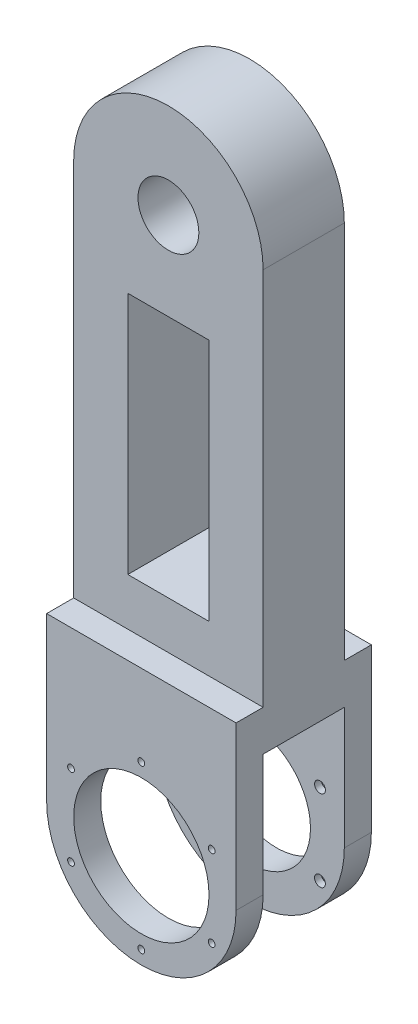
SolidWorks part; units mm, degrees
ref_plane "前视基准面" through (0, 0, 0) normal (0, 0, 1) x (1, 0, 0)
ref_plane "上视基准面" through (0, 0, 0) normal (0, 1, 0) x (1, 0, 0)
ref_plane "右视基准面" through (0, 0, 0) normal (1, 0, 0) x (0, 0, -1)
other "Configuration Table"
sketch "草图1" plane through (0, 0, 0) normal (0, 0, 1) x (1, 0, 0)
  line L1 (-70, -175) -> (70, -175)
  line L2 (-70, -175) -> (-70, 175)
  line L3 (-70, 175) -> (70, 175)
  line L4 (70, -175) -> (70, 175)
  line L5 (-70, -175) -> (70, 175) construction
  line L6 (-70, 175) -> (70, -175) construction
  point P0 (0, 0)
  dimension "D1" = 350
  dimension "D2" = 140
extrude "凸台-拉伸1" add sketch "草图1" along normal blind 60
sketch "草图2" plane through (0, 0, 60) normal (0, 0, 1) x (1, 0, 0)
  line L0 (70, -175) -> (70, 175) construction
  line L1 (-70, 175) -> (70, 175)
  line L2 (-70, 175) -> (-70, 35)
  line L3 (-70, 35) -> (70, 35)
  line L4 (70, 175) -> (70, 35)
  circle A0 centre (0, 105) radius 70
  line M7 (70, 175) -> (-70, 175)
  line M8 (-70, 175) -> (-70, -175)
  dimension "D2" = 140
  dimension "D1" = 140
extrude "切除-拉伸1" cut sketch "草图2" against normal up to next contours A0 L1 M8 | A0 L4 M7
sketch "草图3" plane through (0, 0, 60) normal (0, 0, 1) x (1, 0, 0)
  arc A0 (70, 105) -> (-70, 105) centre (0, 105) ccw construction
  arc A1 (70, 105) -> (-70, 105) centre (0, 105) ccw
  circle A2 centre (0, 105) radius 25
  dimension "D1" = 50
sketch "草图4" plane through (0, -175, 0) normal (0, -1, 0) x (1, 0, 0)
  line L0 (-70, 60) -> (70, 0) construction
  line L1 (-70, 0) -> (70, 60) construction
  line L3 (-70, -20) -> (70, -20)
  line L4 (-70, 0) -> (70, 0)
  line L5 (70, 0) -> (70, 60)
  line L6 (70, 60) -> (-70, 60)
  line L7 (-70, 60) -> (-70, 0)
  line L8 (-70, 0) -> (70, 0)
  line L9 (70, 0) -> (70, 60)
  line L10 (70, 60) -> (-70, 60)
  line L11 (-70, 60) -> (-70, 0)
  line L12 (-70, -20) -> (-70, 80)
  line L13 (-70, 80) -> (70, 80)
  line L14 (70, -20) -> (70, 80)
  line L15 (-70, -20) -> (70, 80) construction
  line L16 (-70, 80) -> (70, -20) construction
  point P2 (0, 30)
  dimension "D2" = 140
  dimension "D3" = 100
  dimension "D1" = 0
extrude "凸台-拉伸3" add sketch "草图4" along normal blind 30 contours L3 L14 L13 L12
sketch "草图5" plane through (0, -205, 0) normal (0, -1, 0) x (1, 0, 0)
  line L0 (70, 60) -> (-70, 60) construction
  line L1 (-70, 60) -> (-70, 80) construction
  line L2 (-70, 80) -> (70, 80) construction
  line L3 (70, 80) -> (70, 60) construction
  line L4 (-70, 80) -> (-70, -20)
  line L5 (-70, -20) -> (70, -20)
  line L6 (70, -20) -> (70, 80)
  line L7 (70, 80) -> (-70, 80)
  line L8 (-70, 80) -> (-70, -20)
  line L9 (-70, -20) -> (70, -20)
  line L10 (70, -20) -> (70, 80)
  line L11 (70, 80) -> (-70, 80)
  line L12 (-70, -20) -> (-70, 0) construction
  line L13 (-70, 0) -> (70, 0) construction
  line L14 (70, 0) -> (70, -20) construction
  line L15 (70, -20) -> (-70, -20) construction
  line L16 (70, 60) -> (-70, 60)
  line L17 (-70, 60) -> (-70, 80)
  line L18 (-70, 80) -> (70, 80)
  line L19 (70, 80) -> (70, 60)
  line L20 (-70, -20) -> (-70, 0)
  line L21 (-70, 0) -> (70, 0)
  line L22 (70, 0) -> (70, -20)
  line L23 (70, -20) -> (-70, -20)
  line M5 (-70, 80) -> (-70, -20)
  line M6 (-70, -20) -> (70, -20)
  line M7 (70, -20) -> (70, 80)
  line M8 (70, 80) -> (-70, 80)
  dimension "D1" = 0
extrude "凸台-拉伸4" add sketch "草图5" along normal blind 160 contours L16 L10 M8 M5 | L21 M5 M6 M7
sketch "草图7" plane through (0, 0, -20) normal (0, 0, -1) x (-1, 0, 0)
  line L0 (70, -365) -> (70, -175) construction
  line L1 (-70, -365) -> (70, -365)
  line L2 (-70, -365) -> (-70, -225)
  line L3 (-70, -225) -> (70, -225)
  line L4 (70, -365) -> (70, -225)
  circle A0 centre (0, -295) radius 70
  line M8 (-70, -365) -> (70, -365)
  line M9 (70, -365) -> (70, -175)
  dimension "D2" = 140
  dimension "D1" = 140
extrude "切除-拉伸3" cut sketch "草图7" against normal through all contours A0 L2 M8 | A0 L1 M9
sketch "草图8" plane through (0, 0, 0) normal (0, 0, -1) x (-1, 0, 0)
  line L0 (0, 0) -> (0, -100) construction
  line L2 (-30, -140) -> (30, -140)
  line L3 (-70, 105) -> (-70, -175)
  line L4 (-70, -175) -> (70, -175)
  line L5 (70, -175) -> (70, 105)
  line L6 (-70, 105) -> (-70, -175)
  line L7 (-70, -175) -> (70, -175)
  line L8 (70, -175) -> (70, 105)
  line L9 (-30, -140) -> (-30, 40)
  line L10 (-30, 40) -> (30, 40)
  line L11 (30, -140) -> (30, 40)
  line L12 (-30, -140) -> (30, 40) construction
  line L13 (-30, 40) -> (30, -140) construction
  arc A1 (70, 105) -> (-70, 105) centre (0, 105) ccw
  arc A2 (70, 105) -> (-70, 105) centre (0, 105) ccw
  point P7 (0, -50)
  dimension "D2" = 100
  dimension "D3" = 60
  dimension "D4" = 180
  dimension "D1" = 0
extrude "切除-拉伸4" cut sketch "草图8" against normal through all contours L9 L2 L11 L10
sketch "草图9" plane through (0, 0, -20) normal (0, 0, -1) x (-1, 0, 0)
  line L3 (70, -295) -> (70, -175)
  line L4 (70, -175) -> (-70, -175)
  line L5 (-70, -175) -> (-70, -295)
  line L6 (70, -295) -> (70, -175)
  line L7 (70, -175) -> (-70, -175)
  line L8 (-70, -175) -> (-70, -295)
  circle A0 centre (0, -295) radius 45
  arc A1 (-70, -295) -> (70, -295) centre (0, -295) ccw
  arc A2 (-70, -295) -> (70, -295) centre (0, -295) ccw
  dimension "D2" = 90
  dimension "D1" = 0
extrude "切除-拉伸5" cut sketch "草图9" against normal up to next contours A0
sketch "草图10" plane through (0, 0, 80) normal (0, 0, 1) x (1, 0, 0)
  line L3 (-70, -175) -> (-70, -295)
  line L4 (70, -295) -> (70, -175)
  line L5 (70, -175) -> (-70, -175)
  line L6 (-70, -175) -> (-70, -295)
  line L7 (70, -295) -> (70, -175)
  line L8 (70, -175) -> (-70, -175)
  circle A0 centre (0, -295) radius 50
  arc A1 (-70, -295) -> (70, -295) centre (0, -295) ccw
  arc A2 (-70, -295) -> (70, -295) centre (0, -295) ccw
  dimension "D2" = 100
  dimension "D1" = 0
extrude "切除-拉伸6" cut sketch "草图10" against normal up to next contours A0
sketch "草图11" plane through (0, 0, 60) normal (0, 0, 1) x (1, 0, 0)
  line L1 (-10, 95) -> (10, 95)
  line L2 (-10, 95) -> (-10, 115)
  line L3 (-10, 115) -> (10, 115)
  line L4 (10, 95) -> (10, 115)
  line L5 (-10, 95) -> (10, 115) construction
  line L6 (-10, 115) -> (10, 95) construction
  arc A0 (70, 105) -> (-70, 105) centre (0, 105) ccw construction
  arc A1 (70, 105) -> (-70, 105) centre (0, 105) ccw
  dimension "D1" = 20
  dimension "D2" = 20
extrude "切除-拉伸7" cut sketch "草图11" against normal through all contours L1 L4 L3 L2
sketch "草图12" plane through (0, 0, -20) normal (0, 0, -1) x (-1, 0, 0)
  circle A0 centre (0, -295) radius 45 construction
  circle A1 centre (0, -295) radius 45
  circle A2 centre (0, -295) radius 60
  circle A3 centre (0, -355) radius 2.5
  circle A4 centre (-51.9615, -325) radius 2.5
  circle A5 centre (-51.9615, -265) radius 2.5
  circle A6 centre (0, -235) radius 2.5
  circle A7 centre (51.9615, -265) radius 2.5
  circle A8 centre (51.9615, -325) radius 2.5
  point P18 (0, -295)
  dimension "D1" = 120
  dimension "D2" = 5
  dimension "D3" = 6
sketch "草图13" plane through (0, 0, 80) normal (0, 0, 1) x (1, 0, 0)
  circle A1 centre (-51.9615, -265) radius 2.5
  circle A2 centre (-51.9615, -265) radius 2.5
  circle A3 centre (0, -235) radius 2.5
  circle A4 centre (0, -235) radius 2.5
  circle A5 centre (51.9615, -265) radius 2.5
  circle A6 centre (51.9615, -265) radius 2.5
  circle A7 centre (51.9615, -325) radius 2.5
  circle A8 centre (51.9615, -325) radius 2.5
  circle A9 centre (0, -355) radius 2.5
  circle A10 centre (0, -355) radius 2.5
  circle A11 centre (0, -295) radius 60
  circle A12 centre (0, -295) radius 60
  circle A13 centre (0, -295) radius 45
  circle A14 centre (0, -295) radius 45
  circle A15 centre (-51.9615, -325) radius 2.5
  circle A16 centre (-51.9615, -325) radius 2.5
  dimension "D1" = 0
  dimension "D2" = 0
  dimension "D3" = 0
  dimension "D4" = 0
  dimension "D5" = 0
  dimension "D6" = 0
  dimension "D7" = 0
  dimension "D8" = 0
extrude "切除-拉伸10" cut sketch "草图13" against normal up to next contours A8 | A6 | A4 | A2 | A16 | A10
sketch "草图14" plane through (0, 0, 60) normal (0, 0, -1) x (-1, 0, 0)
  circle A0 centre (0, -295) radius 50 construction
  circle A1 centre (-51.9615, -325) radius 2.5 construction
  circle A2 centre (0, -295) radius 50
  circle A3 centre (-51.9615, -325) radius 2.5
  circle A4 centre (-51.9615, -325) radius 4
  circle A5 centre (-51.9615, -265) radius 4
  circle A6 centre (0, -295) radius 50
  circle A7 centre (0, -235) radius 4
  circle A8 centre (0, -295) radius 50
  circle A9 centre (51.9615, -265) radius 4
  circle A10 centre (0, -295) radius 50
  circle A11 centre (51.9615, -325) radius 4
  circle A12 centre (0, -295) radius 50
  circle A13 centre (0, -355) radius 4
  circle A14 centre (0, -295) radius 50
  point P25 (0, -295)
  dimension "D1" = 8
  dimension "D2" = 6
extrude "切除-拉伸11" cut sketch "草图14" against normal blind 5 contours A9 | A11 | A13 | A7 | A5 | A4
ref_plane "基准面1" through (10, 95, 60) normal (1, 0, 0) x (0, 0, -1)
sketch "草图16" plane through (0, 0, 60) normal (0, 0, 1) x (1, 0, 0)
  line L0 (-10, 115) -> (10, 95) construction
  line L4 (10, 95) -> (10, 115)
  line L5 (-10, 95) -> (10, 95)
  line L6 (-10, 115) -> (-10, 95)
  line L7 (10, 115) -> (-10, 115)
  line L8 (10, 95) -> (10, 115)
  line L9 (-10, 95) -> (10, 95)
  line L10 (-10, 115) -> (-10, 95)
  line L11 (10, 115) -> (-10, 115)
  circle A0 centre (0, 105) radius 22.5
  dimension "D2" = 45
  dimension "D1" = 0
extrude "切除-拉伸12" cut sketch "草图16" against normal blind 50 contours A0 | L8 L11 L10 L9
sketch "草图17" plane through (0, 0, 10) normal (0, 0, 1) x (1, 0, 0)
  circle A0 centre (0, 105) radius 22.5 construction
  circle A1 centre (0, 105) radius 22.5
  circle A2 centre (0, 105) radius 17.5
  circle A3 centre (0, 122.5) radius 1.5
  circle A4 centre (15.1554, 113.75) radius 1.5
  circle A5 centre (15.1554, 96.25) radius 1.5
  circle A6 centre (0, 87.5) radius 1.5
  circle A7 centre (-15.1554, 96.25) radius 1.5
  circle A8 centre (-15.1554, 113.75) radius 1.5
  point P18 (0, 105)
  dimension "D1" = 35
  dimension "D2" = 3
  dimension "D3" = 6
extrude "切除-拉伸13" cut sketch "草图17" against normal through all contours A2 A8 | A2 A7 | A2 A7 | A2 A3 | A2 A3 | A2 A4 | A2 A4 | A2 A5 | A2 A5 | A2 A6 | A2 A6
sketch "草图18" plane through (0, 0, -20) normal (0, 0, -1) x (-1, 0, 0)
  circle A0 centre (0, -235) radius 4 construction
  circle A1 centre (-51.9615, -265) radius 4 construction
  circle A2 centre (-51.9615, -325) radius 4 construction
  circle A3 centre (0, -355) radius 4 construction
  circle A4 centre (51.9615, -325) radius 4 construction
  circle A5 centre (51.9615, -265) radius 4 construction
  circle A6 centre (0, -235) radius 4
  circle A7 centre (-51.9615, -265) radius 4
  circle A8 centre (-51.9615, -325) radius 4
  circle A9 centre (0, -355) radius 4
  circle A10 centre (51.9615, -325) radius 4
  circle A11 centre (51.9615, -265) radius 4
extrude "切除-拉伸14" cut sketch "草图18" against normal blind 5
sketch "草图19" plane through (0, 0, -20) normal (0, 0, -1) x (-1, 0, 0)
  circle A0 centre (-51.9615, -265) radius 2.5 construction
  circle A1 centre (-51.9615, -325) radius 2.5 construction
  circle A2 centre (0, -355) radius 2.5 construction
  circle A3 centre (51.9615, -325) radius 2.5 construction
  circle A4 centre (51.9615, -265) radius 2.5 construction
  circle A5 centre (0, -235) radius 2.5 construction
  circle A6 centre (-51.9615, -265) radius 2.5
  circle A7 centre (-51.9615, -325) radius 2.5
  circle A8 centre (0, -355) radius 2.5
  circle A9 centre (51.9615, -325) radius 2.5
  circle A10 centre (51.9615, -265) radius 2.5
  circle A11 centre (0, -235) radius 2.5
extrude "切除-拉伸15" cut sketch "草图19" against normal through all
sketch "草图20" plane through (0, 0, 0) normal (0, 0, 1) x (1, 0, 0)
  line L3 (-70, -175) -> (-70, -295)
  line L4 (70, -175) -> (-70, -175)
  line L5 (70, -295) -> (70, -175)
  line L6 (-70, -175) -> (-70, -295)
  line L7 (70, -175) -> (-70, -175)
  line L8 (70, -295) -> (70, -175)
  circle A0 centre (-51.9615, -265) radius 4 construction
  arc A1 (-70, -295) -> (70, -295) centre (0, -295) ccw
  arc A2 (-70, -295) -> (70, -295) centre (0, -295) ccw
  circle A3 centre (-51.9615, -265) radius 4
  circle A4 centre (0.0406, -234.9962) radius 4
  circle A5 centre (52.0256, -265.0295) radius 4
  circle A6 centre (52.0086, -325.0665) radius 4
  circle A7 centre (0.0065, -355.0703) radius 4
  circle A8 centre (-51.9786, -325.037) radius 4
  point P20 (0.0235, -295.0333)
  dimension "D1" = 0
  dimension "D2" = 6
extrude "切除-拉伸16" cut sketch "草图20" against normal blind 5 contours A7 | A6 | A8 | A3 | A4 | A5
